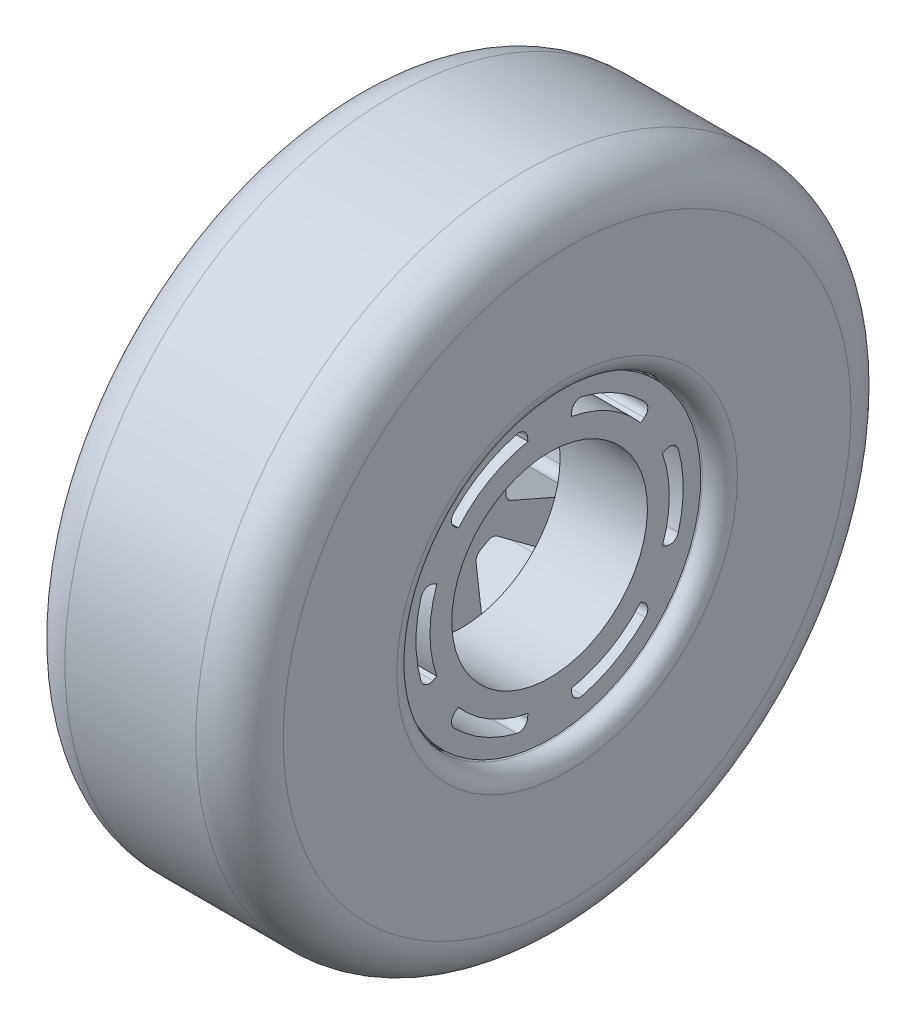
SolidWorks part; units mm, degrees
other "hub"
other "tire" parameters "D2"=11.5642, "D3"=26.3439, "D4"=9.1812, "D5"=9.1812, "D6"=9.2095, "D1"=0, "D7"=6
ref_plane "Front" through (0, 0, 0) normal (0, 0, 1) x (1, 0, 0)
ref_plane "Top" through (0, 0, 0) normal (0, 1, 0) x (1, 0, 0)
ref_plane "Right" through (0, 0, 0) normal (1, 0, 0) x (0, 0, -1)
sketch "Sketch1" plane through (0, 0, 0) normal (1, 0, 0) x (0, 0, -1)
  circle A0 centre (0, 0) radius 37.5 construction
  circle A1 centre (0, 0) radius 37.5
sketch "Sketch2" plane through (0, 0, 0) normal (0, 0, 1) x (1, 0, 0)
  line L0 (0, -37.5) -> (0, 37.5) construction
  line L1 (0, -37.5) -> (0, 37.5) construction
  line L2 (7.5, -37.5) -> (-7.5, -37.5)
  line L5 (0, 0) -> (-50000, 0) construction
  line L6 (-12.5, -32.5) -> (-12.5, -19.5)
  line L7 (-10.5, -17.5) -> (-9, -17.5)
  line L8 (12.5, -19.5) -> (12.5, -32.5)
  line L9 (9, -17.5) -> (9, -21.5) construction
  line L10 (9, -21.5) -> (-9, -21.5) construction
  line L11 (-9, -21.5) -> (-9, -17.5) construction
  line L12 (9, -17.5) -> (10.5, -17.5)
  line L13 (9, -17.5) -> (5, -21.5)
  line L14 (-9, -17.5) -> (-5, -21.5)
  line L15 (5, -21.5) -> (-5, -21.5)
  arc A0 (-12.5, -32.5) -> (-7.5, -37.5) centre (-7.5, -32.5) ccw
  arc A1 (12.5, -32.5) -> (7.5, -37.5) centre (7.5, -32.5) cw
  arc A2 (10.5, -17.5) -> (12.5, -19.5) centre (10.5, -19.5) cw
  arc A3 (-10.5, -17.5) -> (-12.5, -19.5) centre (-10.5, -19.5) ccw
  point P5 (0, -37.5)
  point P9 (0, -37.5)
  point P23 (0, -21.5)
  point P25 (-4.6543, -21.5)
  point P27 (0, -21.5)
  dimension "D1" = 5
  dimension "D2" = 2
  dimension "D3" = 20
  dimension "D4" = 4
  dimension "D5" = 25
  dimension "D6" = 45
  dimension "D7" = 45
  dimension "D8" = 10
revolve "Revolve2" add sketch "Sketch2" angle 360 about L5
sketch "Sketch3" plane through (0, 0, 0) normal (0, 0, 1) x (1, 0, 0)
  line L0 (10.5, 0) -> (-10.5, 0)
  line L2 (10.5, -17.3) -> (8.9172, -17.3)
  line L3 (8.9172, -17.3) -> (4.9172, -21.3)
  line L4 (4.9172, -21.3) -> (-4.9172, -21.3)
  line L5 (-4.9172, -21.3) -> (-8.9172, -17.3)
  line L6 (-8.9172, -17.3) -> (-10.5, -17.3)
  line L7 (10.5, 0) -> (10.5, -17.3)
  line L8 (-12.5, -19.5) -> (-12.5, -32.5)
  line L9 (-7.5, -37.5) -> (7.5, -37.5)
  line L10 (12.5, -32.5) -> (12.5, -19.5)
  line L11 (10.5, -17.5) -> (9, -17.5)
  line L12 (9, -17.5) -> (5, -21.5)
  line L13 (5, -21.5) -> (-5, -21.5)
  line L14 (-5, -21.5) -> (-9, -17.5)
  line L15 (-9, -17.5) -> (-10.5, -17.5)
  line L16 (-12.5, -19.5) -> (-12.5, -32.5) construction
  line L17 (-7.5, -37.5) -> (7.5, -37.5) construction
  line L18 (12.5, -32.5) -> (12.5, -19.5) construction
  line L19 (10.5, -17.5) -> (9, -17.5) construction
  line L20 (9, -17.5) -> (5, -21.5) construction
  line L21 (5, -21.5) -> (-5, -21.5) construction
  line L22 (-5, -21.5) -> (-9, -17.5) construction
  line L23 (-9, -17.5) -> (-10.5, -17.5) construction
  line L24 (-10.5, 0) -> (-10.5, -17.3)
  arc A4 (-12.5, -32.5) -> (-7.5, -37.5) centre (-7.5, -32.5) ccw
  arc A5 (7.5, -37.5) -> (12.5, -32.5) centre (7.5, -32.5) ccw
  arc A6 (12.5, -19.5) -> (10.5, -17.5) centre (10.5, -19.5) ccw
  arc A7 (-10.5, -17.5) -> (-12.5, -19.5) centre (-10.5, -19.5) ccw
  arc A8 (-12.5, -32.5) -> (-7.5, -37.5) centre (-7.5, -32.5) ccw construction
  arc A9 (7.5, -37.5) -> (12.5, -32.5) centre (7.5, -32.5) ccw construction
  arc A10 (12.5, -19.5) -> (10.5, -17.5) centre (10.5, -19.5) ccw construction
  arc A11 (-10.5, -17.5) -> (-12.5, -19.5) centre (-10.5, -19.5) ccw construction
  point P13 (0, 0)
  dimension "D1" = 0
  dimension "D2" = 0.2
revolve "Revolve3" add sketch "Sketch3" angle 360 about L0
sketch "Sketch4" plane through (-10.5, 0, 0) normal (-1, 0, 0) x (0, 0, 1)
  line L0 (0, 5) -> (0, 15.3) construction
  line L1 (0, 0) -> (-2.6568, 15.0676) construction
  line L2 (0, 0) -> (2.6568, 15.0676) construction
  line L3 (-2.6568, 15.0676) -> (-1.5, 4.7697)
  line L4 (2.6568, 15.0676) -> (1.5, 4.7697)
  line L5 (-1.5, 4.7697) -> (1.5, 4.7697) construction
  line L6 (14.3773, 5.2329) -> (4.8807, 1.0858)
  line L7 (11.7205, 9.8347) -> (3.3807, 3.6839)
  line L8 (11.7205, -9.8347) -> (3.3807, -3.6839)
  line L9 (14.3773, -5.2329) -> (4.8807, -1.0858)
  line L10 (-2.6568, -15.0676) -> (-1.5, -4.7697)
  line L11 (2.6568, -15.0676) -> (1.5, -4.7697)
  line L12 (-14.3773, -5.2329) -> (-4.8807, -1.0858)
  line L13 (-11.7205, -9.8347) -> (-3.3807, -3.6839)
  line L14 (-11.7205, 9.8347) -> (-3.3807, 3.6839)
  line L15 (-14.3773, 5.2329) -> (-4.8807, 1.0858)
  circle A0 centre (0, 0) radius 15.3
  circle A1 centre (0, 0) radius 17.3
  circle A2 centre (0, 0) radius 17.3 construction
  circle A3 centre (0, 0) radius 5
  point P7 (0, 4.7697)
  point P34 (0, 0)
  dimension "D2" = 10
  dimension "D3" = 2
  dimension "D4" = 20
  dimension "D5" = 10
  dimension "D6" = 3
extrude "Cut-Extrude1" cut sketch "Sketch4" against normal through all contours A3 L3 A0 L14 | A3 L7 A0 L4 | A3 L9 A0 L6 | A3 L11 A0 L8 | A3 L13 A0 L10 | A3 L15 A0 L12
sketch "Sketch5" plane through (10.5, 0, 0) normal (1, 0, 0) x (0, 0, -1)
  circle A0 centre (0, 0) radius 11.2
  dimension "D1" = 22.4
extrude "Cut-Extrude2" cut sketch "Sketch5" against normal blind 10
fillet "Fillet1" radius 1 24 edges at (-5, 1.0858, -4.8807) (-5, -1.0858, -4.8807) (-5, 3.6839, -3.3807) (-5, 4.7697, -1.5) (-5, 4.7697, 1.5) (-5, 3.6839, 3.3807) (-5, 1.0858, 4.8807) (-5, -1.0858, 4.8807) (-5, -3.6839, 3.3807) (-5, -4.7697, 1.5) (-5, -4.7697, -1.5) (-5, -3.6839, -3.3807) (0, -5.2329, -14.3773) (0, 5.2329, -14.3773) (0, -9.8347, -11.7205) (0, -15.0676, -2.6568) (0, -15.0676, 2.6568) (0, -9.8347, 11.7205) (0, -5.2329, 14.3773) (0, 5.2329, 14.3773) (0, 9.8347, 11.7205) (0, 15.0676, 2.6568) (0, 15.0676, -2.6568) (0, 9.8347, -11.7205)
fillet "Fillet2" radius 1 48 edges at (-10.5, 9.9026, 11.2346) (-10.5, 13.2502, 7.65) (-10.5, 14.6807, 2.9586) (-10.5, 9.7494, 2.0594) (-10.5, 4.9316, 1.705) (-10.5, 4.3301, 2.5) (-10.5, 3.9424, 3.4184) (-10.5, 6.6582, 7.4135) (-10.5, 14.6807, -2.9586) (-10.5, 13.2502, -7.65) (-10.5, 9.9026, -11.2346) (-10.5, 6.6582, -7.4135) (-10.5, 3.9424, -3.4184) (-10.5, 4.3301, -2.5) (-10.5, 4.9316, -1.705) (-10.5, 9.7494, -2.0594) (-10.5, 4.7781, -14.1932) (-10.5, 0, -15.3) (-10.5, -4.7781, -14.1932) (-10.5, -3.0912, -9.4729) (-10.5, -0.9892, -5.1234) (-10.5, 0, -5) (-10.5, 0.9892, -5.1234) (-10.5, 3.0912, -9.4729) (-10.5, -9.9026, -11.2346) (-10.5, -13.2502, -7.65) (-10.5, -14.6807, -2.9586) (-10.5, -9.7494, -2.0594) (-10.5, -4.9316, -1.705) (-10.5, -4.3301, -2.5) (-10.5, -3.9424, -3.4184) (-10.5, -6.6582, -7.4135) (-10.5, -14.6807, 2.9586) (-10.5, -13.2502, 7.65) (-10.5, -9.9026, 11.2346) (-10.5, -6.6582, 7.4135) (-10.5, -3.9424, 3.4184) (-10.5, -4.3301, 2.5) (-10.5, -4.9316, 1.705) (-10.5, -9.7494, 2.0594) (-10.5, -4.7781, 14.1932) (-10.5, 0, 15.3) (-10.5, 4.7781, 14.1932) (-10.5, 3.0912, 9.4729) (-10.5, 0.9892, 5.1234) (-10.5, 0, 5) (-10.5, -0.9892, 5.1234) (-10.5, -3.0912, 9.4729)
sketch "Sketch6" plane through (0.5, 0, 0) normal (1, 0, 0) x (0, 0, -1)
  circle A0 centre (0, 0) radius 11.2
  circle A1 centre (0, 0) radius 13.7
  circle A2 centre (0, 0) radius 11.2 construction
  dimension "D2" = 2.5
extrude "Boss-Extrude3" add sketch "Sketch6" along normal up to surface (10 mm away) up to face at (10.5, 0, 0)
equation "\"D5@Sketch4\"=\"D4@Sketch4\"/2"
